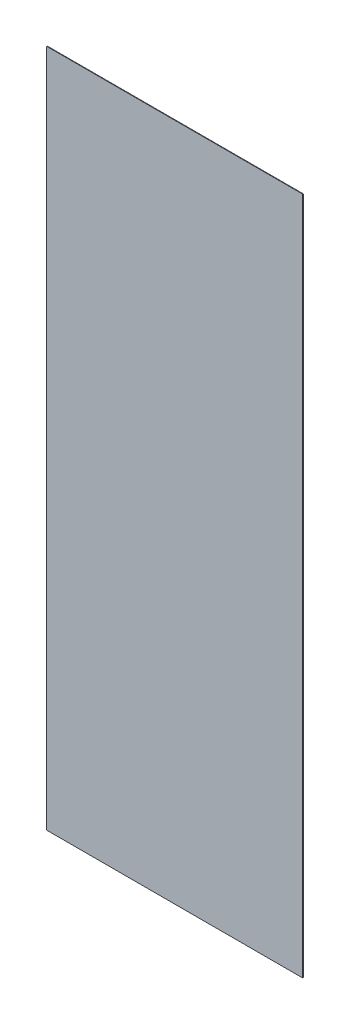
SolidWorks part; units mm, degrees
ref_plane "Front Plane" through (0, 0, 0) normal (0, 0, 1) x (1, 0, 0)
ref_plane "Top Plane" through (0, 0, 0) normal (0, 1, 0) x (1, 0, 0)
ref_plane "Right Plane" through (0, 0, 0) normal (1, 0, 0) x (0, 0, -1)
other "Configuration Table"
sketch "Sketch1" plane through (0, 0, 0) normal (0, 0, 1) x (1, 0, 0)
  line L1 (1.5, 120) -> (698.5, 120)
  line L2 (1.5, 120) -> (1.5, 1968.5)
  line L3 (1.5, 1968.5) -> (698.5, 1968.5)
  line L4 (698.5, 120) -> (698.5, 1968.5)
extrude "OVEN_dis_arka_1" add sketch "Sketch1" against normal blind 1.5 from offset 818.5 separate body
